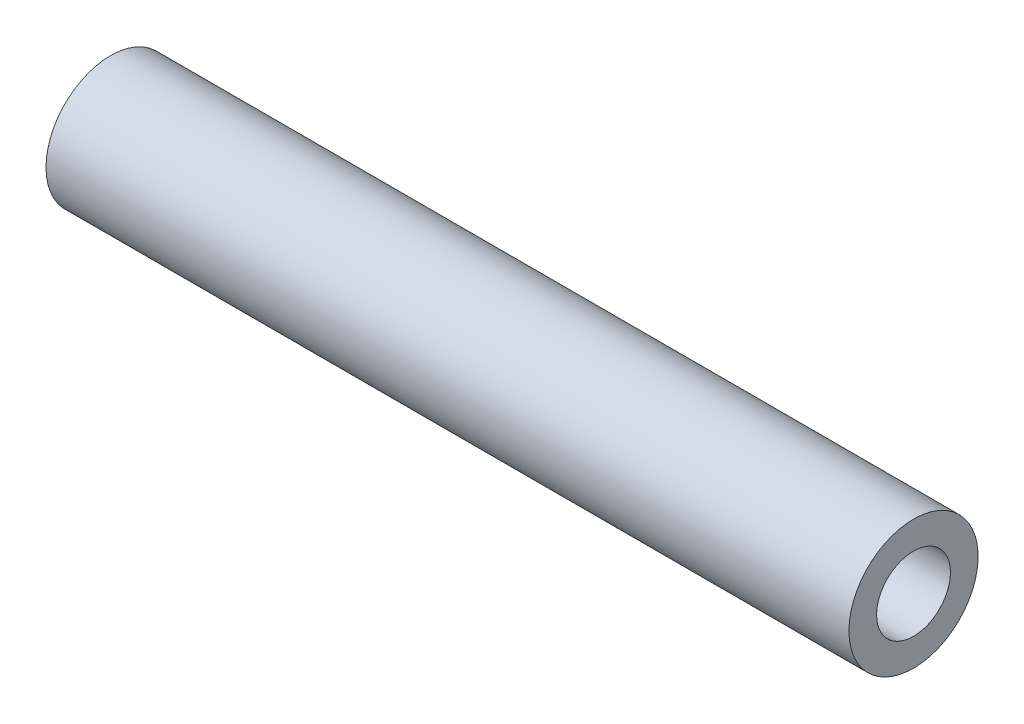
SolidWorks part; units mm, degrees
material "ﾎﾟﾘｵｷｼﾒﾁﾚﾝ(POM)ｱｾﾀｰﾙ共重合体"
ref_plane "正面" through (0, 0, 0) normal (0, 0, 1) x (1, 0, 0)
ref_plane "平面" through (0, 0, 0) normal (0, 1, 0) x (1, 0, 0)
ref_plane "右側面" through (0, 0, 0) normal (1, 0, 0) x (0, 0, -1)
sketch "ｽｹｯﾁ1" plane through (0, 0, 0) normal (0, 0, 1) x (1, 0, 0)
  line L0 (0, 0) -> (50000, 0) construction
  line L1 (-43.5, 7) -> (43.5, 7)
  line L2 (-43.5, 7) -> (-43.5, 4)
  line L3 (-43.5, 4) -> (43.5, 4)
  line L4 (43.5, 7) -> (43.5, 4)
  point P4 (0, 7)
  dimension "D1" = 87
  dimension "D2" = 8
  dimension "D3" = 14
revolve "回転1" add sketch "ｽｹｯﾁ1" angle 360 about L0
